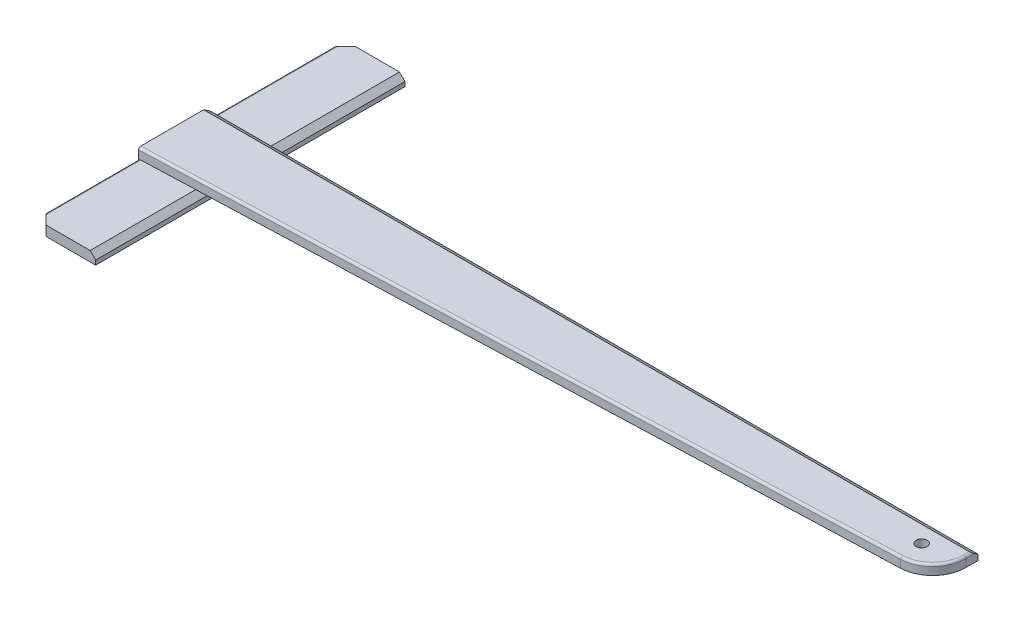
SolidWorks part; units mm, degrees
ref_plane "Front Plane" through (0, 0, 0) normal (0, 0, 1) x (1, 0, 0)
ref_plane "Top Plane" through (0, 0, 0) normal (0, 1, 0) x (1, 0, 0)
ref_plane "Right Plane" through (0, 0, 0) normal (1, 0, 0) x (0, 0, -1)
sketch "Sketch1" plane through (0, 0, 0) normal (0, 1, 0) x (1, 0, 0)
  line L1 (0, 0) -> (1397, 0)
  line L2 (0, 0) -> (0, 7112)
  line L3 (0, 7112) -> (1397, 7112)
  line L4 (1397, 0) -> (1397, 7112)
  dimension "D1" = 1397
  dimension "D2" = 7112
extrude "Boss-Extrude1" add sketch "Sketch1" along normal blind 228.6
chamfer "Chamfer1" distance 127 angle 45 1 edges at (1397, 228.6, -3556)
chamfer "Chamfer3" distance 254 angle 45 1 edges at (0, 114.3, -7112)
chamfer "Chamfer4" distance 254 angle 45 1 edges at (0, 114.3, 0)
sketch "Sketch3" plane through (0, 228.6, 0) normal (0, 1, 0) x (1, 0, 0)
  line L0 (17653, 3016.2877) -> (0, 2381.2877)
  line L1 (0, 2381.2877) -> (0, 4032.2877)
  line L2 (0, 4032.2877) -> (17653, 4032.2877)
  line L7 (0, 6858) -> (0, 254) construction
  line L8 (17653, 4032.2877) -> (17653, 3016.2877)
  dimension "D1" = 17653
  dimension "D2" = 1651
  dimension "D3" = 1016
extrude "Boss-Extrude2" add sketch "Sketch3" along normal blind 228.6
chamfer "Chamfer5" distance 101.6 distance2 152.4 1 edges at (8826.5, 457.2, -4032.2877)
fillet "Fillet1" radius 762 1 edges at (17653, 342.9, -3016.2877)
fillet "Fillet2" radius 50.8 5 edges at (17653, 457.2, -3815.6291) (17439.4145, 457.2, -3222.3284) (0, 228.6, -5445.1438) (0, 228.6, -1317.6438) (8459.1962, 457.2, -2685.5753)
sketch "Sketch4" plane through (0, 457.2, 0) normal (0, 1, 0) x (1, 0, 0)
  circle A0 centre (16891, 3497.863) radius 127
  point P3 (0, 0)
  point P5 (16886.9264, 3490.3723)
  dimension "D1" = 254
  dimension "D2" = 762
  dimension "D3" = 508
extrude "Cut-Extrude1" cut sketch "Sketch4" against normal through all
